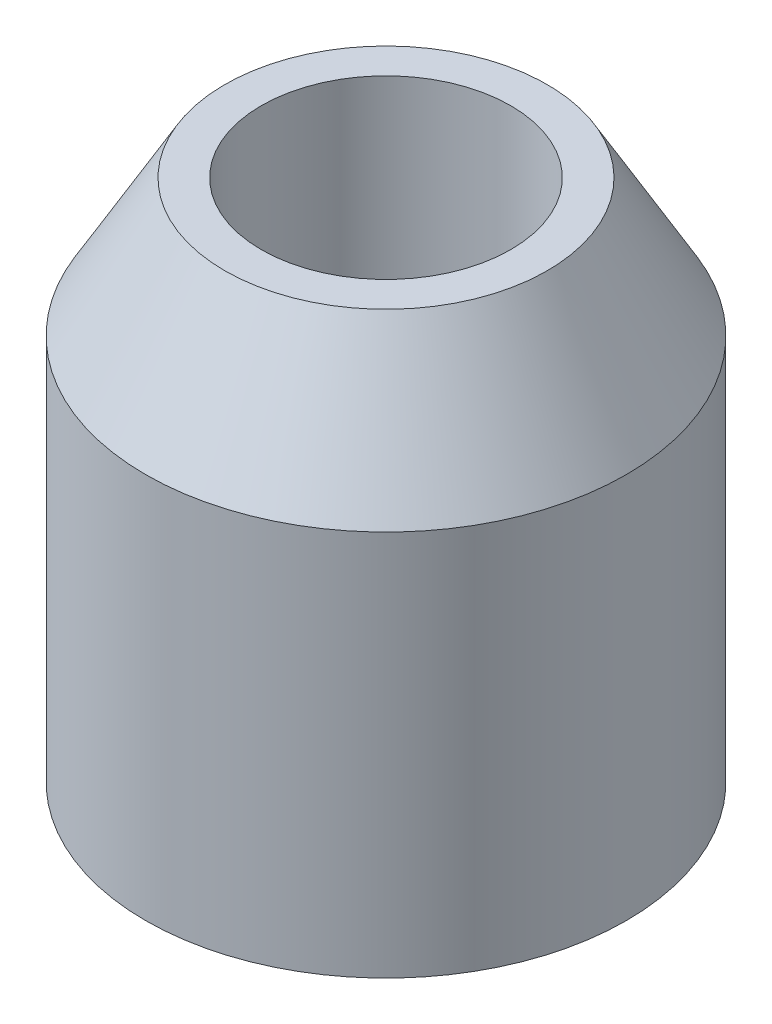
SolidWorks part; units mm, degrees
ref_plane "Front Plane" through (0, 0, 0) normal (0, 0, 1) x (1, 0, 0)
ref_plane "Top Plane" through (0, 0, 0) normal (0, 1, 0) x (1, 0, 0)
ref_plane "Right Plane" through (0, 0, 0) normal (1, 0, 0) x (0, 0, -1)
sketch "Sketch1" plane through (0, 0, 0) normal (0, 0, 1) x (1, 0, 0)
  line L0 (0, 63.0704) -> (0, 0) construction
  line L7 (19.75, 31.7417) -> (19.75, 0)
  line L8 (19.75, 0) -> (16.75, 0)
  line L9 (16.75, 0) -> (16.75, 28)
  line L11 (16.75, 28) -> (10.25, 28)
  line L12 (10.25, 28) -> (10.25, 43)
  line L13 (10.25, 43) -> (13.25, 43)
  line L14 (13.25, 43) -> (19.75, 31.7417)
  point P1 (19.75, 31.9405)
  point P11 (9.7082, 28)
  point P12 (0, 63.0704)
  dimension "D1" = 33.5
  dimension "D2" = 28
  dimension "D3" = 3
  dimension "D4" = 3
  dimension "D5" = 15
  dimension "D6" = 60
  dimension "D7" = 20.5
revolve "Revolve1" add sketch "Sketch1" angle 360 about L0
